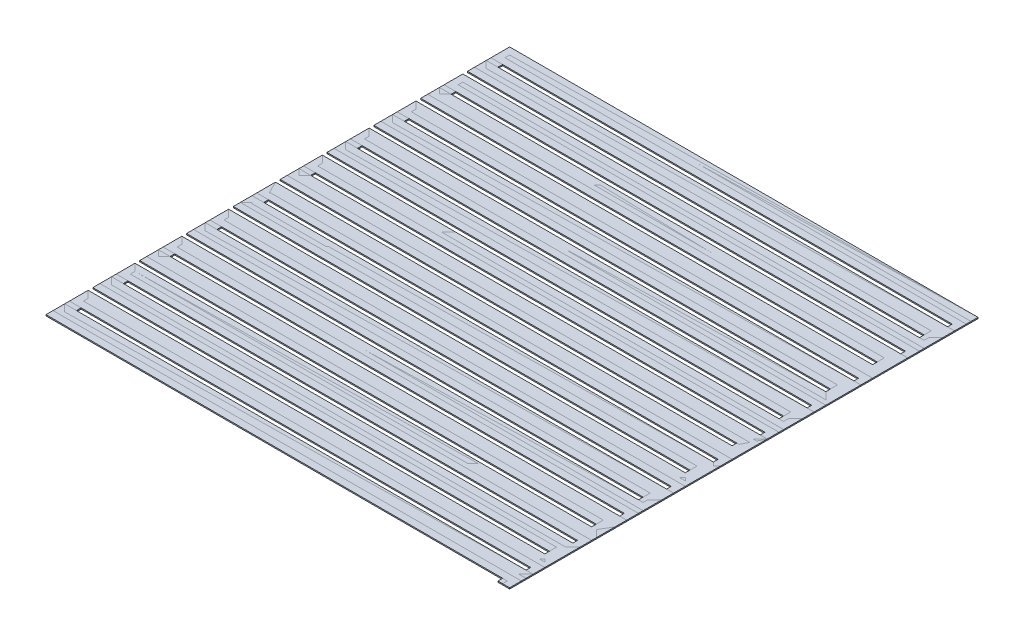
SolidWorks part; units mm, degrees
ref_plane "Front Plane" through (0, 0, 0) normal (0, 0, 1) x (1, 0, 0)
ref_plane "Top Plane" through (0, 0, 0) normal (0, 1, 0) x (1, 0, 0)
ref_plane "Right Plane" through (0, 0, 0) normal (1, 0, 0) x (0, 0, -1)
sketch "Base Guidlines" plane through (0, 0, 0) normal (0, 1, 0) x (1, 0, 0)
  line L0 (-4.5961, 9.2) -> (-4.5961, 8.5)
  line L1 (-10, -10) -> (10, -10)
  line L2 (-10, -10) -> (-10, 10)
  line L3 (-10, 10) -> (10, 10)
  line L4 (10, -10) -> (10, 10)
  line L5 (-10, -10) -> (10, 10) construction
  line L6 (-10, 10) -> (10, -10) construction
  line L7 (-10, 10) -> (10, 10)
  line L8 (-10, 10) -> (-10, 9.2)
  line L9 (-10, 9.2) -> (10, 9.2)
  line L10 (10, 10) -> (10, 9.2)
  line L11 (-4.5961, -9.2) -> (-4.5961, -8.5)
  line L12 (-10, -10) -> (10, -10)
  line L13 (-10, -10) -> (-10, -9.2)
  line L14 (-10, -9.2) -> (10, -9.2)
  line L15 (10, -10) -> (10, -9.2)
  line L17 (-10, -9.2) -> (10, -9.2)
  line L18 (-10, -9.2) -> (-10, -8.5)
  line L19 (-10, -8.5) -> (10, -8.5)
  line L20 (10, -9.2) -> (10, -8.5)
  line L21 (-10, 9.2) -> (10, 9.2)
  line L22 (-10, 9.2) -> (-10, 8.5)
  line L23 (-10, 8.5) -> (10, 8.5)
  line L24 (10, 9.2) -> (10, 8.5)
  point P0 (0, 0)
  dimension "D1" = 20
  dimension "D2" = 20
  dimension "D3" = 0.7
  dimension "D4" = 0.7
sketch "Mirror axis x" plane through (0, 0, 0) normal (0, 1, 0) x (1, 0, 0)
  line L0 (-10, 0) -> (10, 0)
  line L1 (-10, -10) -> (-10, 10) construction
  line L2 (10, -10) -> (10, 10) construction
sketch "TopBlock" plane through (0, 0, 0) normal (0, 1, 0) x (1, 0, 0)
  line L0 (-10, 10) -> (10, -10) construction
  line L1 (-10, 10) -> (-9.7, 10)
  line L2 (-10, 10) -> (-10, 9.7)
  line L3 (10, 9.2) -> (10, 9.5)
  line L4 (-9.7, 10) -> (10, 10)
  line L5 (-9.7, 9.7) -> (-9.7, 9.5)
  line L6 (-10, 9.2) -> (-9.7, 9.2)
  line L7 (-10, 9.2) -> (-10, 9.5)
  line L8 (-9.7, 9.5) -> (9.7, 9.5)
  line L10 (-10, 9.7) -> (-10, 9.5)
  line L11 (-9.7, 9.7) -> (10, 9.7)
  line L12 (10, 9.7) -> (10, 10)
  line L13 (10, -10) -> (10, 10) construction
  line L14 (10, 9.2) -> (9.7, 9.2)
  line L15 (10, 9.5) -> (9.7, 9.5)
  line L24 (9.7, 9.2) -> (-9.7, 9.2)
  dimension "D1" = 0.3
  dimension "D2" = 0.3
extrude "Extruded object" add sketch "TopBlock" along normal blind 0.05
sketch "Mirror axis y" plane through (0, 0, 0) normal (0, 1, 0) x (1, 0, 0)
  line L0 (0, 10) -> (0, -10)
  line L3 (10, 10) -> (-10, 10) construction
  point P4 (0, 0)
  point P5 (0, 0)
  dimension "D1" = 20
sketch "GapandInbetween" plane through (0, 0, 0) normal (0, 1, 0) x (1, 0, 0)
  line L0 (10, 9.2) -> (10, 9)
  line L1 (10, -10) -> (10, 10) construction
  line L2 (10, 9) -> (10, 8.7)
  line L3 (-9.7, 8.5) -> (-9.7, 8.7)
  line L4 (9.7, 9) -> (9.7, 9.2)
  line L5 (-10, 9.2) -> (10, 9.2) construction
  line L6 (9.7, 9.2) -> (10, 9.2)
  line L7 (10, 8.7) -> (-9.7, 8.7)
  line L8 (-10, -10) -> (-10, 10) construction
  line L9 (9.7, 9) -> (-10, 9)
  line L10 (-10, 9) -> (-10, 8.7)
  line L11 (-10, 8.7) -> (-10, 8.5)
  line L12 (-9.7, 8.5) -> (10, 8.5)
  line L13 (-10, 8.5) -> (10, 8.5) construction
  line L14 (-10, 8.5) -> (-10, 8.2)
  line L15 (-10, 8.2) -> (9.7, 8.2)
  line L16 (9.7, 8.2) -> (10, 8.2)
  line L17 (10, 8.2) -> (10, 8.5)
  dimension "D1" = 0.2
  dimension "D2" = 0.3
  dimension "D3" = 0.3
  dimension "D4" = 0.3
  dimension "D5" = 0.3
extrude "Boss-Extrude2" add sketch "GapandInbetween" along normal blind 0.05
pattern_linear "LPattern1" count 19 spacing 1 along (0, 0, 1) of "Boss-Extrude2"
sketch "Sketch1" plane through (0, 0, 0) normal (0, 1, 0) x (1, 0, 0)
  line L1 (10, -9.8) -> (10, -10)
  line L2 (9.7, -9.8) -> (9.7, -10)
  line L3 (9.7, -10) -> (10, -10)
  line L4 (10, -9.8) -> (9.7, -9.8)
  line L5 (-10, -9.8) -> (10, -9.8) construction
  dimension "D1" = 0.2
extrude "Boss-Extrude3" add sketch "Sketch1" along normal blind 0.05
sketch "Sketch2" plane through (0, 0, 0) normal (0, 1, 0) x (1, 0, 0)
  line L1 (-10, 10) -> (10, 10)
  line L2 (-10, 10) -> (-10, -10)
  line L3 (-10, -10) -> (10, -10)
  line L4 (10, 10) -> (10, -10)
  dimension "D1" = 20
extrude "Boss-Extrude4" add sketch "Sketch2" along normal blind 0.05 separate body
sketch "Sketch3" plane through (0, 0, 0) normal (0, 1, 0) x (1, 0, 0)
  line L0 (10, -10) -> (10, 10) construction
  line L1 (10, 9.5) -> (-9.5, 9.5)
  line L2 (10, 9.5) -> (10, 9)
  line L3 (10, 9) -> (-9.5, 9)
  line L4 (-9.5, 9.5) -> (-9.5, 9)
  line L5 (10, 10) -> (-10, 10) construction
  line L6 (-10, 10) -> (-10, -10) construction
  point P10 (0, 0)
  point P11 (0, 0)
  point P12 (0, 0)
  dimension "D1" = 0.5
  dimension "D2" = 0.5
  dimension "D3" = 0.5
sketch "Sketch4" plane through (0, 0, 0) normal (0, 1, 0) x (1, 0, 0)
  line L0 (-10, 10) -> (-10, -10) construction
  line L1 (-10, 8.5) -> (9.5, 8.5)
  line L2 (-10, 8.5) -> (-10, 8)
  line L3 (-10, 8) -> (9.5, 8)
  line L4 (9.5, 8.5) -> (9.5, 8)
  line L5 (10, 9) -> (-9.5, 9) construction
  line L6 (10, -10) -> (10, 10) construction
  dimension "D1" = 0.5
  dimension "D2" = 0.5
  dimension "D3" = 0.5
extrude "Cut-Extrude3" cut sketch "Sketch3" along normal blind 0.05
extrude "Cut-Extrude5" cut sketch "Sketch4" along normal blind 0.05
pattern_linear "LPattern2" count 10 spacing 2 along (0, 0, 1) of "Cut-Extrude3"
pattern_linear "LPattern3" count 10 spacing 2 along (0, 0, 1) of "Cut-Extrude5"
